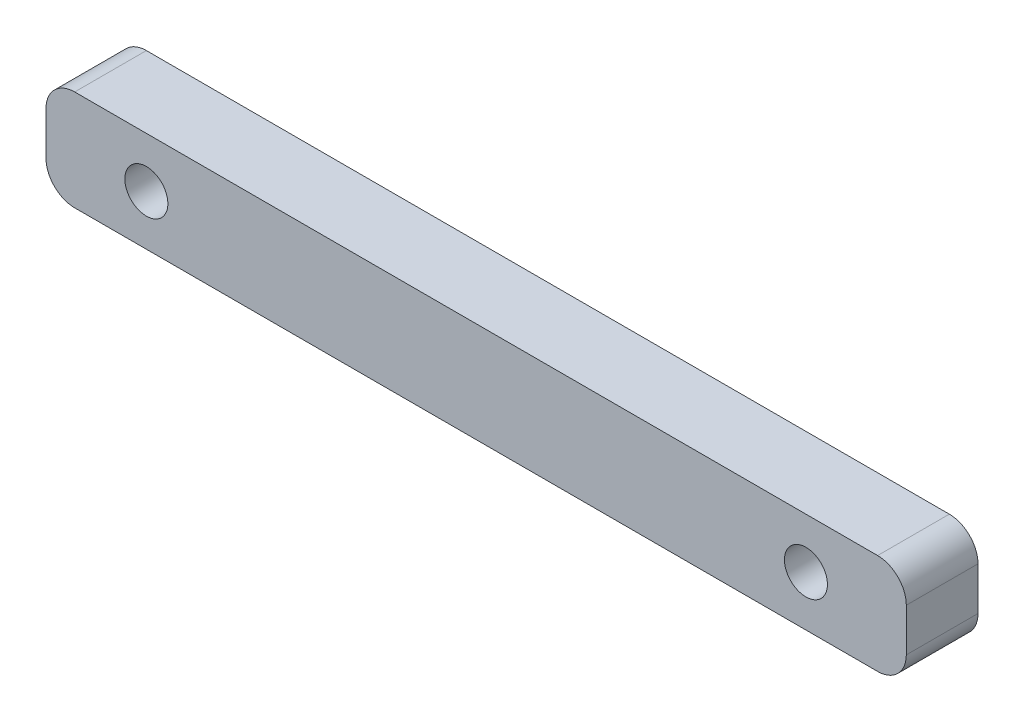
SolidWorks part; units mm, degrees
ref_plane "前视基准面" through (0, 0, 0) normal (0, 0, 1) x (1, 0, 0)
ref_plane "上视基准面" through (0, 0, 0) normal (0, 1, 0) x (1, 0, 0)
ref_plane "右视基准面" through (0, 0, 0) normal (1, 0, 0) x (0, 0, -1)
sketch "草图2" plane through (0, 0, 0) normal (0, 0, 1) x (1, 0, 0)
  line L0 (0, 11.5594) -> (0, -10.7263) construction
  line L1 (-30, -3.5) -> (30, -3.5)
  line L2 (-30, -3.5) -> (-30, 3.5)
  line L3 (-30, 3.5) -> (30, 3.5)
  line L4 (30, -3.5) -> (30, 3.5)
  line L5 (-30, -3.5) -> (30, 3.5) construction
  line L6 (-30, 3.5) -> (30, -3.5) construction
  circle A0 centre (-23, 0) radius 1.5
  circle A1 centre (23, 0) radius 1.5
  point P0 (0, 0)
  dimension "D4" = 3.5
  dimension "D5" = 3
  dimension "D1" = 60
  dimension "D2" = 7
  dimension "D3" = 7
extrude "凸台-拉伸1" add sketch "草图2" along normal blind 5
fillet "圆角5" radius 2 4 edges at (30, 3.5, 2.5) (30, -3.5, 2.5) (-30, 3.5, 2.5) (-30, -3.5, 2.5)
